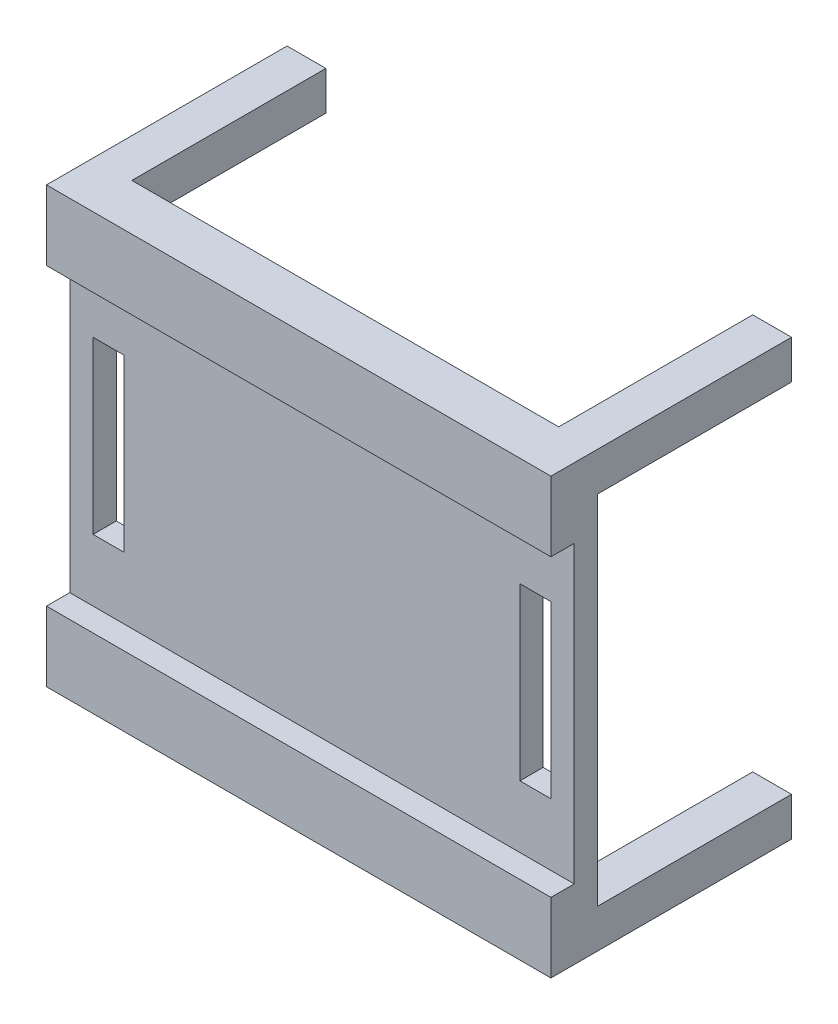
SolidWorks part; units mm, degrees
ref_plane "Plan de face" through (0, 0, 0) normal (0, 0, 1) x (1, 0, 0)
ref_plane "Plan de dessus" through (0, 0, 0) normal (0, 1, 0) x (1, 0, 0)
ref_plane "Plan de droite" through (0, 0, 0) normal (1, 0, 0) x (0, 0, -1)
sketch "Esquisse1" plane through (0, 0, 0) normal (0, 0, 1) x (1, 0, 0)
  line L5 (32.5, -28) -> (-32.5, -28)
  line L6 (32.5, -28) -> (32.5, 28)
  line L11 (32.5, 28) -> (-32.5, 28)
  line L12 (-32.5, -28) -> (-32.5, 28)
  line L13 (32.5, -28) -> (-32.5, 28) construction
  line L14 (32.5, 28) -> (-32.5, -28) construction
  point P0 (0, 0)
  dimension "D1" = 56
  dimension "D2" = 65
extrude "Boss.-Extru.1" add sketch "Esquisse1" along normal blind 6
sketch "Esquisse4" plane through (0, 0, 6) normal (0, 0, 1) x (1, 0, 0)
  line L0 (-32.5, -28) -> (-32.5, 28) construction
  line L1 (32.5, -19) -> (-32.5, -19)
  line L2 (32.5, -19) -> (32.5, 19)
  line L3 (32.5, 19) -> (-32.5, 19)
  line L4 (-32.5, -19) -> (-32.5, 19)
  line L5 (32.5, -19) -> (-32.5, 19) construction
  line L6 (32.5, 19) -> (-32.5, -19) construction
  point P0 (0, 0)
  dimension "D1" = 38
extrude "Enlèv. mat.-Extru.1" cut sketch "Esquisse4" against normal blind 3
sketch "Esquisse5" plane through (0, 0, 0) normal (0, 0, -1) x (-1, 0, 0)
  line L1 (-32.5, 28) -> (-27.5, 28)
  line L2 (-32.5, 28) -> (-32.5, 23)
  line L3 (-32.5, 23) -> (-27.5, 23)
  line L4 (-27.5, 28) -> (-27.5, 23)
  dimension "D1" = 5
extrude "Boss.-Extru.2" add sketch "Esquisse5" along normal blind 25
sketch "Esquisse6" plane through (0, 0, -25) normal (0, 0, -1) x (-1, 0, 0)
  line L0 (-32.5, 28) -> (-32.5, 23) construction
  line L1 (-27.5, 28) -> (-32.5, 28) construction
  circle A0 centre (-29, 24.5) radius 1.1
  dimension "D1" = 2.2
  dimension "D2" = 3.5
  dimension "D3" = 3.5
extrude "Enlèv. mat.-Extru.2" cut sketch "Esquisse6" against normal blind 3
sketch "Esquisse7" plane through (0, 0, 0) normal (0, 0, -1) x (-1, 0, 0)
  line L0 (-27.5, -28) -> (-27.5, 28) construction
  line L1 (0, -28) -> (0, 28) construction
  line L2 (-25.5, -11) -> (-29.5, -11)
  line L3 (-25.5, -11) -> (-25.5, 11)
  line L4 (-25.5, 11) -> (-29.5, 11)
  line L5 (-29.5, -11) -> (-29.5, 11)
  line L6 (-25.5, -11) -> (-29.5, 11) construction
  line L7 (-25.5, 11) -> (-29.5, -11) construction
  line L8 (-27.5, 23) -> (-27.5, 28) construction
  line L10 (-32.5, -28) -> (32.5, -28) construction
  line L11 (-27.5, 28) -> (32.5, 28) construction
  line L12 (25.5, -11) -> (29.5, -11)
  line L13 (29.5, -11) -> (29.5, 11)
  line L14 (25.5, 11) -> (29.5, 11)
  line L15 (25.5, -11) -> (25.5, 11)
  line L16 (-32.5, -28) -> (32.5, -28) construction
  point P3 (-27.5, 0)
  point P9 (0, 0)
  point P12 (-27.5, -26)
  point P13 (-27.5, -28)
  point P15 (-27.5, -26)
  point P19 (0, 28)
  dimension "D1" = 22
  dimension "D2" = 4
extrude "Enlèv. mat.-Extru.3" cut sketch "Esquisse7" against normal through all
mirror "Symétrie1" about plane through (0, 0, 0) normal (0, 1, 0) of "Enlèv. mat.-Extru.2", "Boss.-Extru.2" second plane through (0, 0, 0) second plane normal (1, 0, 0)
